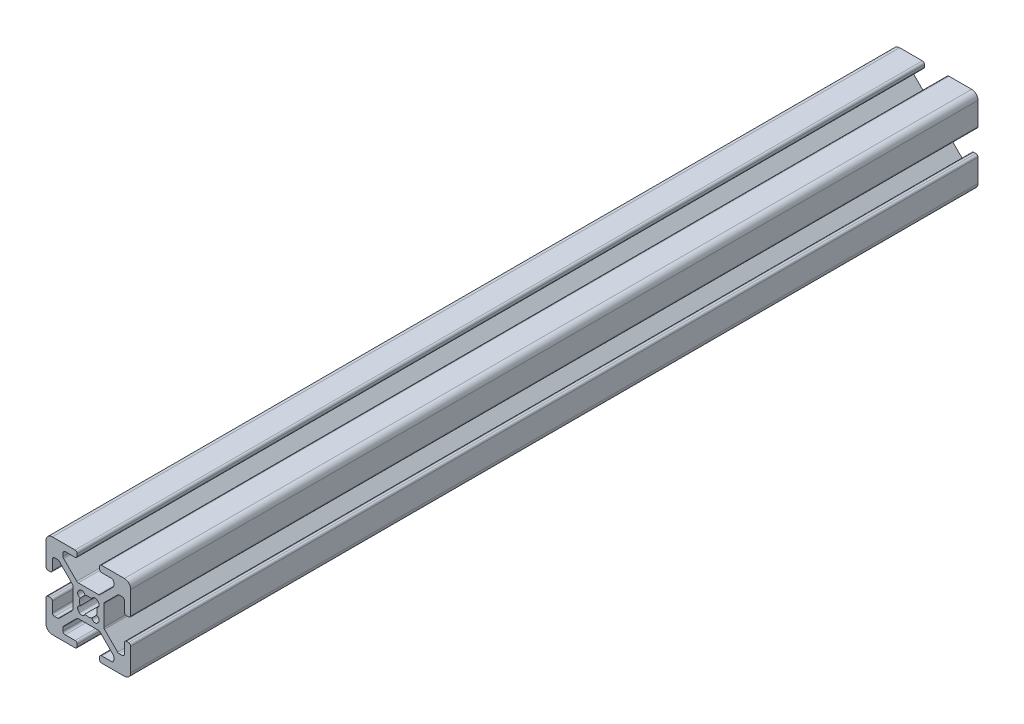
SolidWorks part; units mm, degrees
material "1060 Alloy"
ref_plane "Front Plane" through (0, 0, 0) normal (0, 0, 1) x (1, 0, 0)
ref_plane "Top Plane" through (0, 0, 0) normal (0, 1, 0) x (1, 0, 0)
ref_plane "Right Plane" through (0, 0, 0) normal (1, 0, 0) x (0, 0, -1)
sketch "Sketch2" plane through (0, 0, 0) normal (0, 0, 1) x (1, 0, 0)
  line L0 (-10, -3.138) -> (-10, -8.5)
  line L1 (-8.5, -10) -> (-3.138, -10)
  line L2 (-2.63, -9.492) -> (-2.63, -9.008)
  line L3 (-3.138, -8.5) -> (-5.487, -8.5)
  line L4 (-5.995, -7.992) -> (-5.995, -7.2662)
  line L5 (-5.8462, -6.907) -> (-2.743, -3.8038)
  line L6 (-2.3838, -3.655) -> (2.3841, -3.655)
  line L7 (2.7433, -3.8038) -> (5.8462, -6.9067)
  line L8 (5.995, -7.2659) -> (5.995, -7.992)
  line L9 (5.487, -8.5) -> (3.138, -8.5)
  line L10 (2.63, -9.008) -> (2.63, -9.492)
  line L11 (3.138, -10) -> (8.5, -10)
  line L12 (10, -8.5) -> (10, -3.138)
  line L13 (9.492, -2.63) -> (9.008, -2.63)
  line L14 (8.5, -3.138) -> (8.5, -5.487)
  line L15 (7.992, -5.995) -> (7.2662, -5.995)
  line L16 (6.907, -5.8462) -> (3.8038, -2.743)
  line L17 (3.655, -2.3838) -> (3.655, 2.3841)
  line L18 (3.8038, 2.7433) -> (6.9067, 5.8462)
  line L19 (7.2659, 5.995) -> (7.992, 5.995)
  line L20 (8.5, 5.487) -> (8.5, 3.138)
  line L21 (9.008, 2.63) -> (9.492, 2.63)
  line L22 (10, 3.138) -> (10, 8.5)
  line L23 (8.5, 10) -> (3.138, 10)
  line L24 (2.63, 9.492) -> (2.63, 9.008)
  line L25 (3.138, 8.5) -> (5.487, 8.5)
  line L26 (5.995, 7.992) -> (5.995, 7.2662)
  line L27 (5.8462, 6.907) -> (2.743, 3.8038)
  line L28 (2.3838, 3.655) -> (-2.3841, 3.655)
  line L29 (-2.7433, 3.8038) -> (-5.8462, 6.9067)
  line L30 (-5.995, 7.2659) -> (-5.995, 7.992)
  line L31 (-5.487, 8.5) -> (-3.138, 8.5)
  line L32 (-2.63, 9.008) -> (-2.63, 9.492)
  line L33 (-3.138, 10) -> (-8.5, 10)
  line L34 (-10, 8.5) -> (-10, 3.138)
  line L35 (-9.492, 2.63) -> (-9.008, 2.63)
  line L36 (-8.5, 3.138) -> (-8.5, 5.487)
  line L37 (-7.992, 5.995) -> (-7.2662, 5.995)
  line L38 (-6.907, 5.8462) -> (-3.8038, 2.743)
  line L39 (-3.655, 2.3838) -> (-3.655, -2.3841)
  line L40 (-3.8038, -2.7433) -> (-6.9067, -5.8462)
  line L41 (-7.2659, -5.995) -> (-7.992, -5.995)
  line L42 (-8.5, -5.487) -> (-8.5, -3.138)
  line L43 (-9.008, -2.63) -> (-9.492, -2.63)
  line L44 (-2.1245, 2.3045) -> (-2.3045, 2.1245)
  line L45 (2.3045, 2.1245) -> (2.1245, 2.3045)
  line L46 (2.1245, -2.3045) -> (2.3045, -2.1245)
  line L47 (-2.3045, -2.1245) -> (-2.1245, -2.3045)
  arc A0 (-10, -8.5) -> (-8.5, -10) centre (-8.5, -8.5) ccw
  arc A1 (-3.138, -10) -> (-2.63, -9.492) centre (-3.138, -9.492) ccw
  arc A2 (-2.63, -9.008) -> (-3.138, -8.5) centre (-3.138, -9.008) ccw
  arc A3 (-5.995, -7.992) -> (-5.487, -8.5) centre (-5.487, -7.992) ccw
  arc A4 (-5.8462, -6.907) -> (-5.995, -7.2662) centre (-5.487, -7.2662) ccw
  arc A5 (-2.3838, -3.655) -> (-2.743, -3.8038) centre (-2.3838, -4.163) ccw
  arc A6 (2.7433, -3.8038) -> (2.3841, -3.655) centre (2.3841, -4.163) ccw
  arc A7 (5.995, -7.2659) -> (5.8462, -6.9067) centre (5.487, -7.2659) ccw
  arc A8 (5.487, -8.5) -> (5.995, -7.992) centre (5.487, -7.992) ccw
  arc A9 (3.138, -8.5) -> (2.63, -9.008) centre (3.138, -9.008) ccw
  arc A10 (2.63, -9.492) -> (3.138, -10) centre (3.138, -9.492) ccw
  arc A11 (8.5, -10) -> (10, -8.5) centre (8.5, -8.5) ccw
  arc A12 (10, -3.138) -> (9.492, -2.63) centre (9.492, -3.138) ccw
  arc A13 (9.008, -2.63) -> (8.5, -3.138) centre (9.008, -3.138) ccw
  arc A14 (7.992, -5.995) -> (8.5, -5.487) centre (7.992, -5.487) ccw
  arc A15 (6.907, -5.8462) -> (7.2662, -5.995) centre (7.2662, -5.487) ccw
  arc A16 (3.655, -2.3838) -> (3.8038, -2.743) centre (4.163, -2.3838) ccw
  arc A17 (3.8038, 2.7433) -> (3.655, 2.3841) centre (4.163, 2.3841) ccw
  arc A18 (7.2659, 5.995) -> (6.9067, 5.8462) centre (7.2659, 5.487) ccw
  arc A19 (8.5, 5.487) -> (7.992, 5.995) centre (7.992, 5.487) ccw
  arc A20 (8.5, 3.138) -> (9.008, 2.63) centre (9.008, 3.138) ccw
  arc A21 (9.492, 2.63) -> (10, 3.138) centre (9.492, 3.138) ccw
  arc A22 (10, 8.5) -> (8.5, 10) centre (8.5, 8.5) ccw
  arc A23 (3.138, 10) -> (2.63, 9.492) centre (3.138, 9.492) ccw
  arc A24 (2.63, 9.008) -> (3.138, 8.5) centre (3.138, 9.008) ccw
  arc A25 (5.995, 7.992) -> (5.487, 8.5) centre (5.487, 7.992) ccw
  arc A26 (5.8462, 6.907) -> (5.995, 7.2662) centre (5.487, 7.2662) ccw
  arc A27 (2.3838, 3.655) -> (2.743, 3.8038) centre (2.3838, 4.163) ccw
  arc A28 (-2.7433, 3.8038) -> (-2.3841, 3.655) centre (-2.3841, 4.163) ccw
  arc A29 (-5.995, 7.2659) -> (-5.8462, 6.9067) centre (-5.487, 7.2659) ccw
  arc A30 (-5.487, 8.5) -> (-5.995, 7.992) centre (-5.487, 7.992) ccw
  arc A31 (-3.138, 8.5) -> (-2.63, 9.008) centre (-3.138, 9.008) ccw
  arc A32 (-2.63, 9.492) -> (-3.138, 10) centre (-3.138, 9.492) ccw
  arc A33 (-8.5, 10) -> (-10, 8.5) centre (-8.5, 8.5) ccw
  arc A34 (-10, 3.138) -> (-9.492, 2.63) centre (-9.492, 3.138) ccw
  arc A35 (-9.008, 2.63) -> (-8.5, 3.138) centre (-9.008, 3.138) ccw
  arc A36 (-7.992, 5.995) -> (-8.5, 5.487) centre (-7.992, 5.487) ccw
  arc A37 (-6.907, 5.8462) -> (-7.2662, 5.995) centre (-7.2662, 5.487) ccw
  arc A38 (-3.655, 2.3838) -> (-3.8038, 2.743) centre (-4.163, 2.3838) ccw
  arc A39 (-3.8038, -2.7433) -> (-3.655, -2.3841) centre (-4.163, -2.3841) ccw
  arc A40 (-7.2659, -5.995) -> (-6.9067, -5.8462) centre (-7.2659, -5.487) ccw
  arc A41 (-8.5, -5.487) -> (-7.992, -5.995) centre (-7.992, -5.487) ccw
  arc A42 (-8.5, -3.138) -> (-9.008, -2.63) centre (-9.008, -3.138) ccw
  arc A43 (-9.492, -2.63) -> (-10, -3.138) centre (-9.492, -3.138) ccw
  arc A44 (-1.9358, 0.8037) -> (-1.9358, -0.8037) centre (0, 0) ccw
  arc A45 (-2.3045, 2.1245) -> (-1.9358, 0.8037) centre (-1.748, 1.568) ccw
  arc A46 (-0.8037, 1.9358) -> (-2.1245, 2.3045) centre (-1.568, 1.748) ccw
  arc A47 (0.8037, 1.9358) -> (-0.8037, 1.9358) centre (0, 0) ccw
  arc A48 (2.1245, 2.3045) -> (0.8037, 1.9358) centre (1.568, 1.748) ccw
  arc A49 (1.9358, 0.8037) -> (2.3045, 2.1245) centre (1.748, 1.568) ccw
  arc A50 (1.9358, -0.8037) -> (1.9358, 0.8037) centre (0, 0) ccw
  arc A51 (2.3045, -2.1245) -> (1.9358, -0.8037) centre (1.748, -1.568) ccw
  arc A52 (0.8037, -1.9358) -> (2.1245, -2.3045) centre (1.568, -1.748) ccw
  arc A53 (-0.8037, -1.9358) -> (0.8037, -1.9358) centre (0, 0) ccw
  arc A54 (-2.1245, -2.3045) -> (-0.8037, -1.9358) centre (-1.568, -1.748) ccw
  arc A55 (-1.9358, -0.8037) -> (-2.3045, -2.1245) centre (-1.748, -1.568) ccw
extrude "Boss-Extrude1" add sketch "Sketch2" against normal blind 200
